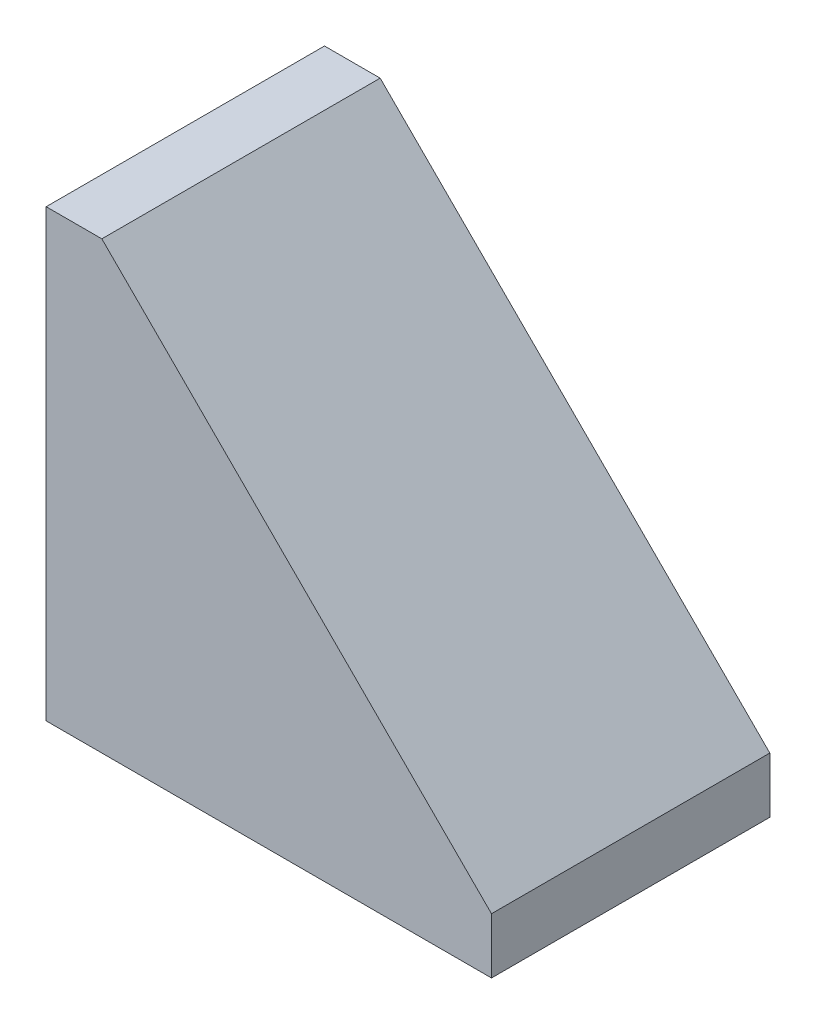
SolidWorks part; units mm, degrees
ref_plane "Front Plane" through (0, 0, 0) normal (0, 0, 1) x (1, 0, 0)
ref_plane "Top Plane" through (0, 0, 0) normal (0, 1, 0) x (1, 0, 0)
ref_plane "Right Plane" through (0, 0, 0) normal (1, 0, 0) x (0, 0, -1)
sketch "Sketch1" plane through (0, 0, 0) normal (0, 0, 1) x (1, 0, 0)
  line L0 (0, 0) -> (0, 25.4)
  line L1 (0, 25.4) -> (3.175, 25.4)
  line L2 (3.175, 25.4) -> (25.4, 3.175)
  line L3 (25.4, 3.175) -> (25.4, 0)
  line L4 (25.4, 0) -> (0, 0)
  dimension "D1" = 25.4
  dimension "D2" = 25.4
  dimension "D3" = 3.175
  dimension "D4" = 3.175
extrude "Boss-Extrude1" add sketch "Sketch1" along normal blind 15.875
